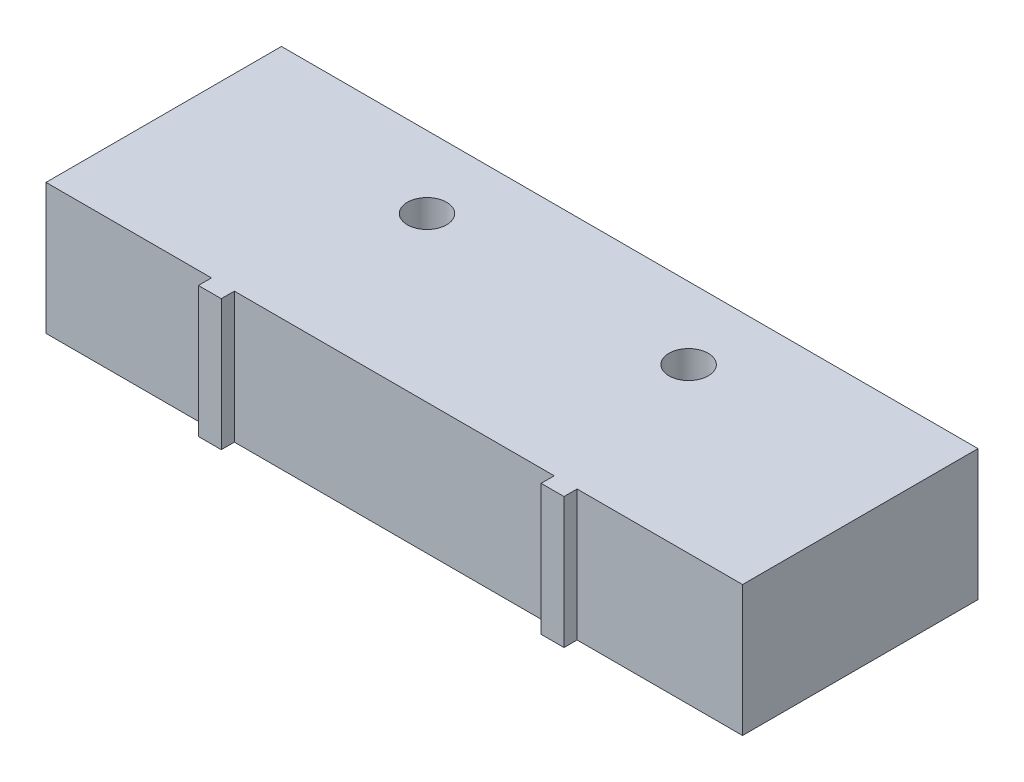
SolidWorks part; units mm, degrees
ref_plane "Front Plane" through (0, 0, 0) normal (0, 0, 1) x (1, 0, 0)
ref_plane "Top Plane" through (0, 0, 0) normal (0, 1, 0) x (1, 0, 0)
ref_plane "Right Plane" through (0, 0, 0) normal (1, 0, 0) x (0, 0, -1)
sketch "Sketch1" plane through (0, 0, 0) normal (0, 1, 0) x (1, 0, 0)
  line L0 (33.25, 25) -> (73.25, 25) construction
  line L1 (0, 0) -> (25.3, 0)
  line L2 (0, 0) -> (0, 36)
  line L3 (0, 36) -> (106.5, 36)
  line L4 (106.5, 0) -> (106.5, 36)
  line L5 (25.3, 0) -> (25.3, -2)
  line L6 (25.3, -2) -> (28.8, -2)
  line L7 (28.8, -2) -> (28.8, 0)
  line L8 (53.25, 36) -> (53.25, 0) construction
  line L9 (77.7, -2) -> (77.7, 0)
  line L10 (81.2, -2) -> (77.7, -2)
  line L11 (0.75, 0) -> (25.3, 0) construction
  line L12 (81.2, 0) -> (81.2, -2)
  line L13 (0.75, 0) -> (0.75, 31.2581) construction
  line L14 (28.8, 0) -> (77.7, 0) construction
  line L15 (28.8, 0) -> (77.7, 0)
  line L16 (81.2, 0) -> (105.75, 0) construction
  line L17 (81.2, 0) -> (106.5, 0)
  line L18 (0.75, 31.2581) -> (35.75, 31.2581) construction
  line L19 (35.75, 31.2581) -> (35.75, 20.0951) construction
  circle A0 centre (33.25, 25) radius 3
  circle A1 centre (73.25, 25) radius 3
  point P19 (27.05, -2)
  point P22 (53.25, 25)
  dimension "D9" = 6
  dimension "D10" = 0.75
  dimension "D1" = 40
  dimension "D2" = 106.5
  dimension "D3" = 36
  dimension "D4" = 105
  dimension "D5" = 26.3
  dimension "D6" = 2
  dimension "D7" = 3.5
  dimension "D8" = 25
  dimension "D11" = 35
extrude "Boss-Extrude2" add sketch "Sketch1" along normal blind 20
